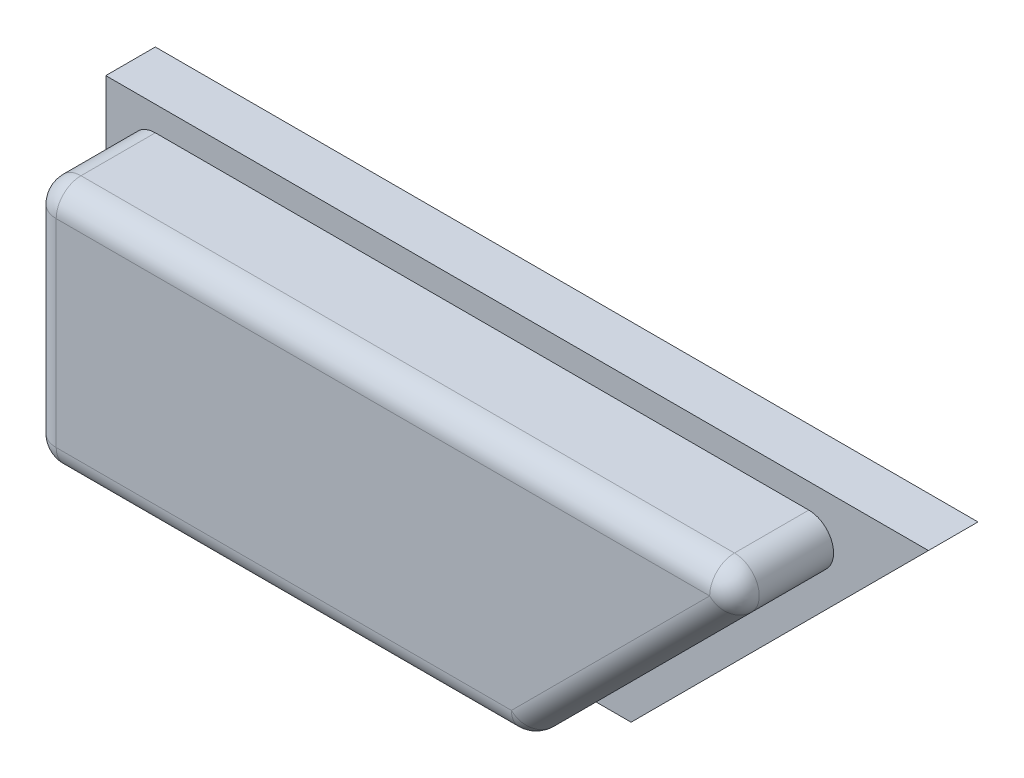
SolidWorks part; units mm, degrees
ref_plane "Front Plane" through (0, 0, 0) normal (0, 0, 1) x (1, 0, 0)
ref_plane "Top Plane" through (0, 0, 0) normal (0, 1, 0) x (1, 0, 0)
ref_plane "Right Plane" through (0, 0, 0) normal (1, 0, 0) x (0, 0, -1)
sketch "Sketch1" plane through (0, 0, 0) normal (0, 0, 1) x (1, 0, 0)
  line L2 (0.1858, 7) -> (6.1858, 7)
  line L6 (-10.4142, 7) -> (0.1858, 7)
  line L7 (-10.4142, 7) -> (-10.4142, 1)
  line L8 (-10.4142, 1) -> (0.1858, 1)
  line L10 (6.1858, 7) -> (0.1858, 1)
  dimension "D1" = 10.6
  dimension "D2" = 10.6
  dimension "D3" = 6
  dimension "D4" = 6
extrude "Boss-Extrude1" add sketch "Sketch1" along normal blind 1
sketch "Sketch3" plane through (0, 0, 1) normal (0, 0, 1) x (1, 0, 0)
  line L0 (-0.6213, 6.5) -> (4.9787, 6.5)
  line L1 (-9.9142, 6.5) -> (-0.6213, 6.5)
  line L2 (-9.9142, 6.5) -> (-9.9142, 1.5)
  line L3 (-9.9142, 1.5) -> (-0.0213, 1.5)
  line L5 (4.9787, 6.5) -> (-0.0213, 1.5)
  line L6 (6.1858, 7) -> (-10.4142, 7) construction
  line L7 (-10.4142, 7) -> (-10.4142, 1) construction
  line L8 (-10.4142, 1) -> (0.1858, 1) construction
  line L9 (0.1858, 1) -> (6.1858, 7) construction
  dimension "D1" = 0.5
  dimension "D2" = 0.5
  dimension "D3" = 0.5
  dimension "D4" = 0.5
  dimension "D5" = 0.5
extrude "Boss-Extrude2" add sketch "Sketch3" along normal blind 2
fillet "Fillet1" radius 0.5 4 edges at (4.9787, 6.5, 2) (-9.9142, 6.5, 2) (-9.9142, 1.5, 2) (-0.0213, 1.5, 2)
fillet "Fillet2" radius 0.5 8 edges at (4.2335, 6.1913, 3) (2.1251, 3.6464, 3) (-0.0371, 1.5381, 3) (-4.8213, 1.5, 3) (-9.7678, 1.6464, 3) (-9.7678, 6.3536, 3) (-9.9142, 4, 3) (-2.8213, 6.5, 3)
